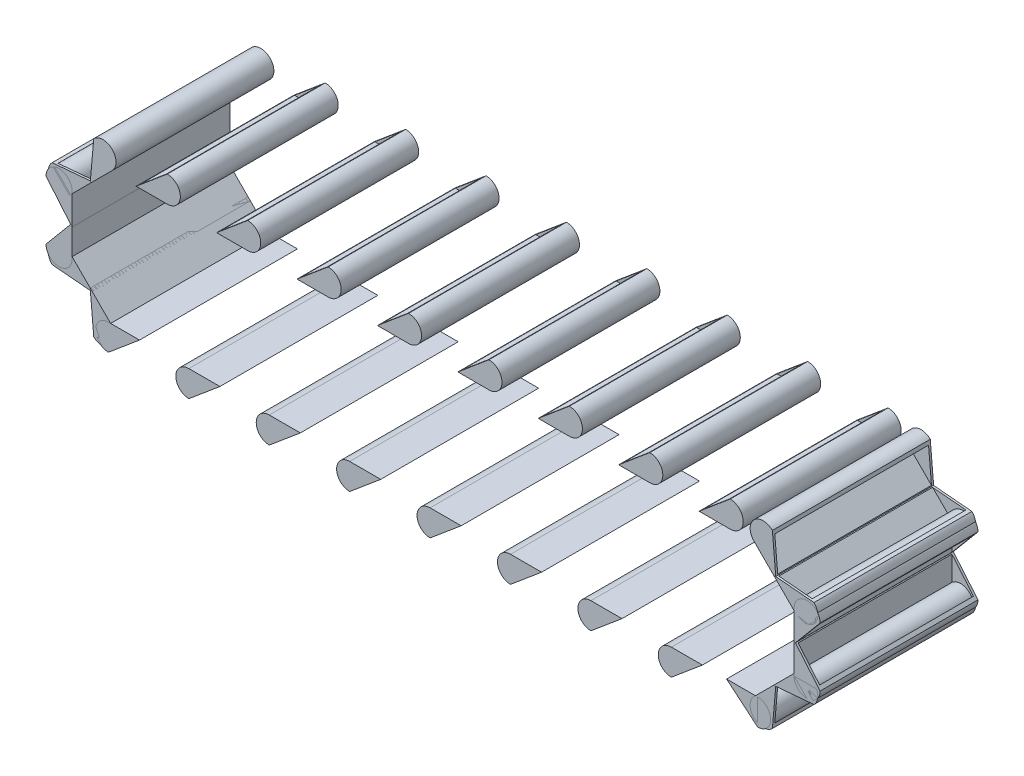
SolidWorks part; units mm, degrees
material "AISI 1035 Steel (SS)"
ref_plane "Front" through (0, 0, 0) normal (0, 0, 1) x (1, 0, 0)
ref_plane "Top" through (0, 0, 0) normal (0, 1, 0) x (1, 0, 0)
ref_plane "Right" through (0, 0, 0) normal (1, 0, 0) x (0, 0, -1)
sketch "Sketch1" plane through (0, 0, 0) normal (0, 0, 1) x (1, 0, 0)
  line L1 (-286.5, 63.5) -> (-256.5, 63.5)
  line L3 (-286.5, 63.5) -> (-256.5, 63.5)
  line L4 (-256.5, 63.5) -> (-286.5, 63.5)
  line L5 (-286.5, 63.5) -> (-256.5, 88.673)
  arc A2 (-256.5, 88.673) -> (-256.5, 63.5) centre (-256.5, 76.0865) cw
  point P3 (0, 0)
extrude "Boss-Extrude1" add sketch "Sketch1" along normal blind 152.4 contours A2 L5 L1
shell "Shell2" thickness 2
sketch "Sketch2" plane through (0, 0, 0) normal (0, 0, 1) x (1, 0, 0)
  line L0 (-284.9075, 0) -> (288.0925, 0) construction
  line L1 (-284.9075, 63.5) -> (288.0925, 63.5)
  line L2 (-284.9075, -63.5) -> (288.0925, -63.5)
  arc A0 (-284.9075, 63.5) -> (-284.9075, -63.5) centre (-284.9075, 0) ccw
  arc A1 (288.0925, -63.5) -> (288.0925, 63.5) centre (288.0925, 0) ccw
  point P3 (1.5925, 0)
  dimension "D2" = 63.5
  dimension "D1" = 286.5
pattern_linear "LPattern1" count 8 spacing 77.6142 along (1, 0, 0) of "Boss-Extrude1", "Shell2"
sketch "Sketch3" plane through (0, 0, 0) normal (0, 0, 1) x (1, 0, 0)
  line L0 (-284.9075, 63.5) -> (-284.9075, -63.5)
  line L1 (288.0925, 63.5) -> (288.0925, -63.5)
ref_plane "Plane1" through (-284.9075, 0, 0) normal (1, 0, 0) x (0, 0, -1)
sketch "Sketch4" plane through (-284.9075, 0, 0) normal (1, 0, 0) x (0, 0, -1)
  line L0 (0, 0) -> (-152.4, 0)
pattern_circular "CirPattern1" count 5 over 180 about axis through (-284.9075, 0, 0) along (0, 0, 1) of bodies 101
pattern_linear "LPattern2" count 8 spacing 77.6142 along (1, 0, 0) of bodies 130
ref_plane "Plane2" through (288.0925, 0, 0) normal (1, 0, 0) x (0, 0, -1)
sketch "Sketch5" plane through (288.0925, 0, 0) normal (1, 0, 0) x (0, 0, -1)
  line L0 (0, 0) -> (130.4638, 0)
mirror "Mirror4" about plane through (0, 0, 0) normal (0, 1, 0) of bodies 127 128 129
mirror "Mirror5" about plane through (0, 0, 0) normal (1, 0, 0) of bodies 127 128 129 130
mirror "Mirror6" about plane through (0, 0, 0) normal (0, 1, 0) of bodies 144 145 146
